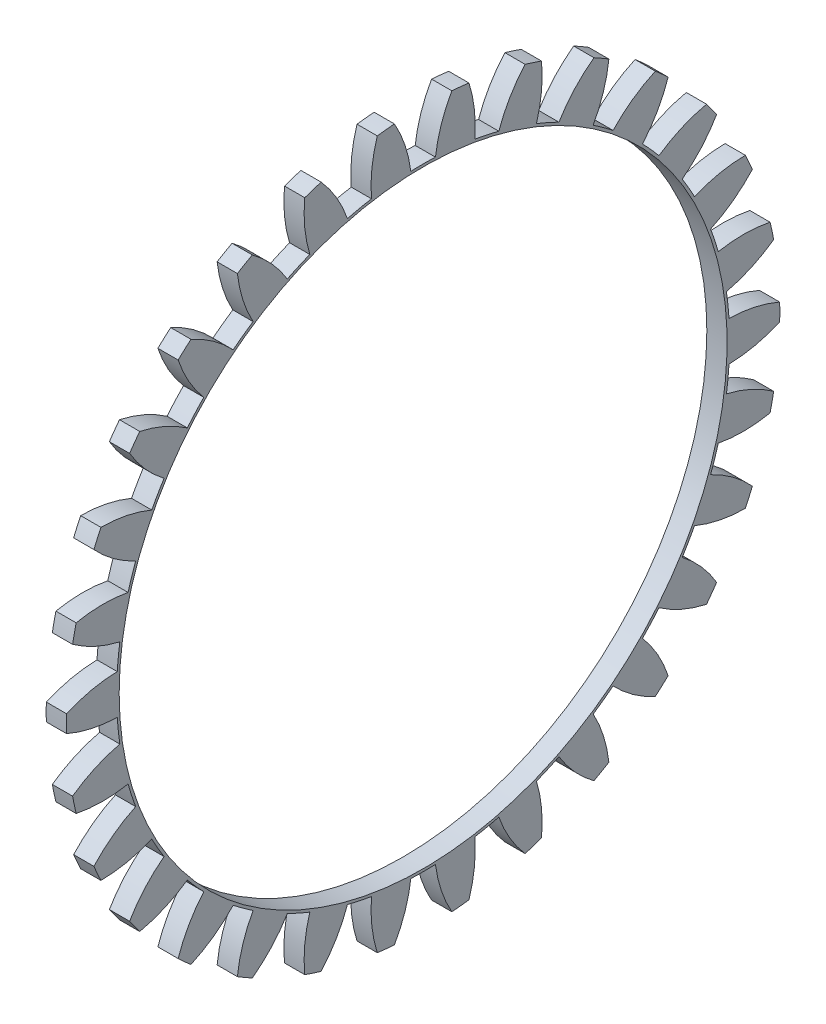
SolidWorks part; units mm, degrees
ref_plane "Plane1" through (0, 0, 0) normal (0, 0, 1) x (1, 0, 0)
ref_plane "Plane2" through (0, 0, 0) normal (0, 1, 0) x (1, 0, 0)
ref_plane "Plane3" through (0, 0, 0) normal (1, 0, 0) x (0, 0, -1)
other "Configuration Table"
sketch "HoldingSke" plane through (0, 0, 0) normal (0, 1, 0) x (1, 0, 0)
  line L0 (0, 0) -> (0.1575, -0.0909)
  line L1 (-15, 0) -> (100, 0) construction
  line L2 (0, 0) -> (-2.1039, 2.3779)
  line L3 (0, 0) -> (-11.863, 4.5341)
  line L4 (0, 0) -> (7.479, 4.318)
  line L5 (0, 0) -> (-46.8476, -17.4728)
  line L6 (0, 0) -> (-4.1448, -2.7965)
  line L7 (-2.1039, 2.3779) -> (8.6586, 51.2059)
  line L8 (-76.2, 54.61) -> (-66.8, 54.61)
  line L9 (-67.7845, 28.3722) -> (-49.3413, 33.142)
  line L10 (-76.2, 71.12) -> (104.1128, 71.12)
  line L11 (0, 0) -> (-5, 0)
  line L12 (-76.2, 101.6) -> (-76.013, 101.6)
  line L13 (24.9733, 27.94) -> (52.9518, 28.4284)
  line L14 (24.9733, 27.94) -> (24.9743, 27.94)
  line L15 (24.9733, 27.94) -> (100.4006, 29.5858)
  line L16 (-63.627, -5.5) -> (-12.827, -5.5)
  circle A0 centre (0, 0) radius 75
  circle A1 centre (0, 0) radius 37.5
  circle A2 centre (0, 0) radius 37.5
  circle A3 centre (0, 0) radius 75
  dimension "MHD" = 75
  dimension "Hub_dia" = 75
  dimension "Bore" = 150
  dimension "MBD" = 150
  dimension "Num_teeth" = 30
  dimension "Pitch" = 0.1818
  dimension "Overall_len" = 50
  dimension "Show_teeth" = 30
  dimension "Thickness" = 5
  dimension "OAL" = 50.0001
  dimension "T_dim" = 9.4
  dimension "Ap" = 14.5
  dimension "H" = 19.05
  dimension "Pitch_radius" = 180.3128
  dimension "Width" = 5
  dimension "Backlash" = 0.187
  dimension "Addendum_fac" = 1
  dimension "Dedendum_fac" = 1.25
  dimension "Clearance_fac" = 0.25
  dimension "Dedendum_add" = 0.001
  dimension "Module" = 5.5
sketch "BasProSke" plane through (0, 0, 0) normal (0, 1, 0) x (1, 0, 0)
  line L0 (-10, 0) -> (60, 0) construction
  line L1 (0, 0) -> (0, 88)
  line L2 (0, 0) -> (5, 0)
  line L3 (5, 0) -> (5, 88)
  line L4 (5, 88) -> (0, 88)
  dimension "Thickness" = 5
  dimension "Diameter" = 176
revolve "Base-Revolve" add sketch "BasProSke" angle 360 about L0
sketch "TooCutSke" plane through (0, 0, 0) normal (1, 0, 0) x (0, 0, -1)
  line L1 (0, 0) -> (0, 107) construction
  line L2 (0, 0) -> (-4.6449, 82.3691) construction
  line L3 (0, 0) -> (-17.227, 163.904) construction
  line L4 (-4.6449, 82.3691) -> (-8.6135, 81.952) construction
  arc A0 (3.0351, 75.5631) -> (-3.0351, 75.5631) centre (0, 0) ccw
  arc A1 (7.0945, 87.739) -> (-7.0945, 87.739) centre (0, 0) ccw
  circle A2 centre (0, 0) radius 82.5 construction
  circle A3 centre (0, 0) radius 79.8722 construction
  arc A4 (-3.0351, 75.5631) -> (-7.0945, 87.739) centre (-35.7731, 71.4132) ccw
  arc A5 (7.0945, 87.739) -> (3.0351, 75.5631) centre (35.7731, 71.4132) ccw
  dimension "Root_dia" = 151.248
  dimension "Overcut_dia" = 176.0508
  dimension "Pitch_dia" = 165
  dimension "Base_dia" = 159.7444
  dimension "Flank_rad" = 33
  dimension "Half_ang" = 6
  dimension "Half_CT" = 3.9905
extrude "ToothCut" cut sketch "TooCutSke" along normal through all
fillet "Breaks" [suppressed] radius 0.11
fillet "RootFillets" [suppressed] radius 1.376
pattern_circular "TeethCuts" count 30 every 12 about axis through (-10, 0, 0) along (1, 0, 0) of "ToothCut", "RootFillets", "Breaks"
sketch "HubNeaOneSke" plane through (0, 0, 0) normal (-1, 0, 0) x (0, 0, 1)
  circle A0 centre (0, 0) radius 37.5
  dimension "Diameter" = 75
extrude "HubNearOne" [suppressed] add sketch "HubNeaOneSke" along normal blind 45.0001
sketch "HubNeaBotSke" plane through (0, 0, 0) normal (-1, 0, 0) x (0, 0, 1)
  circle A0 centre (0, 0) radius 37.5
  dimension "Diameter" = 75
extrude "HubNearBoth" [suppressed] add sketch "HubNeaBotSke" along normal blind 22.5
ref_plane "FarPln" through (5, 0, 0) normal (1, 0, 0) x (0, 0, -1)
sketch "HubFarSke" plane through (5, 0, 0) normal (1, 0, 0) x (0, 0, -1)
  circle A0 centre (0, 0) radius 37.5
  dimension "Diameter" = 75
extrude "HubFar" [suppressed] add sketch "HubFarSke" along normal blind 22.5
sketch "BorSke" plane through (0, 0, 0) normal (1, 0, 0) x (0, 0, -1)
  circle A0 centre (0, 0) radius 75
  dimension "Diameter" = 150
extrude "Bore" cut sketch "BorSke" along normal mid plane 100.0001
sketch "KeySke" plane through (0, 0, 0) normal (1, 0, 0) x (0, 0, -1)
  line L0 (-20, 0) -> (-20, 84.4)
  line L1 (-20, 84.4) -> (20, 84.4)
  line L2 (20, 84.4) -> (20, 0)
  line L3 (0, 0) -> (0, 34) construction
  line L4 (-20, 0) -> (20, 0)
  dimension "Offset" = 84.4
  dimension "Width" = 40
extrude "Keyway" [suppressed] cut sketch "KeySke" along normal mid plane 100.0001
pattern_circular "Keyway2" [suppressed] count 2 every 90 about axis through (-10, 0, 0) along (1, 0, 0)
equation "' \"Module@HoldingSke\" = 6.35"
equation "' \"Num_teeth@HoldingSke\" = 12"
equation "' \"Ap@HoldingSke\" =  20"
equation "' \"Ap@HoldingSke\" = 20"
equation "' \"Width@HoldingSke\" = 0.5 * 25.4"
equation "' \"Hub_dia@HoldingSke\"= 1 * 25.4"
equation "' \"Hub_dia@HoldingSke\" = 1 * 25.4"
equation "' \"Overall_len@HoldingSke\" = 1.0 * 25.4"
equation "' \"Bore@HoldingSke\" = 0.75 * 25.4"
equation "' \"T_dim@HoldingSke\" = 0.1 * 25.4"
equation "' \"Width@KeySke\" = 0.25 * 25.4"
equation "' \"Show_teeth@HoldingSke\" = 13"
equation "' \"Backlash@HoldingSke\" = 0.009 * 25.4"
equation "' \"Addendum_fac@HoldingSke\" = 1.0"
equation "' \"Dedendum_fac@HoldingSke\" = 1.25"
equation "' \"Dedendum_add@HoldingSke\" = 0.00005 * 25.4"
equation "' \"Clearance_fac@HoldingSke\" = 0.25"
equation "\"Pitch@HoldingSke\" = 1 / \"Module@HoldingSke\""
equation "\"Overcut_dia@TooCutSke\" = (\"Num_teeth@HoldingSke\" + 2 * \"Addendum_fac@HoldingSke\") / \"Pitch@HoldingSke\" + 0.002 * 25.4"
equation "\"Pitch_dia@TooCutSke\" = \"Num_teeth@HoldingSke\" / \"Pitch@HoldingSke\""
equation "\"Base_dia@TooCutSke\" = \"Num_teeth@HoldingSke\" / \"Pitch@HoldingSke\" * cos((\"Ap@HoldingSke\"  * 3.14159265 / 180))"
equation "\"Root_dia@TooCutSke\" = (\"Num_teeth@HoldingSke\" + 2) / \"Pitch@HoldingSke\" - 2 * (\"Addendum_fac@HoldingSke\" + \"Dedendum_fac@HoldingSke\") / \"Pitch@HoldingSke\" - \"Dedendum_add@HoldingSke\" * 2"
equation "\"Half_ang@TooCutSke\" = 180 / \"Num_teeth@HoldingSke\""
equation "\"Half_CT@TooCutSke\" = \"Num_teeth@HoldingSke\" / \"Pitch@HoldingSke\" * sin((3.14159265 / 2 / \"Num_teeth@HoldingSke\")) / 2 - 7 * \"Backlash@HoldingSke\" / 4"
equation "\"Flank_rad@TooCutSke\" = \"Num_teeth@HoldingSke\" / \"Pitch@HoldingSke\" / 5"
equation "\"Radius@RootFillets\" = \"Clearance_fac@HoldingSke\" / \"Pitch@HoldingSke\" + \"Dedendum_add@HoldingSke\""
equation "\"Break_rad@Breaks\" = 0.02 / \"Pitch@HoldingSke\""
equation "\"Thickness@HoldingSke\" = \"Width@HoldingSke\""
equation "\"OAL@HoldingSke\" = \"Thickness@HoldingSke\""
equation "\"MHD@HoldingSke\" = (\"Num_teeth@HoldingSke\" + 2) / \"Pitch@HoldingSke\" - 2 * (\"Addendum_fac@HoldingSke\" + \"Dedendum_fac@HoldingSke\")  / \"Pitch@HoldingSke\" - \"Dedendum_add@HoldingSke\" * 2"
equation "\"MBD@HoldingSke\" = (\"Num_teeth@HoldingSke\" + 2) / \"Pitch@HoldingSke\" - 2 * (\"Addendum_fac@HoldingSke\" + \"Dedendum_fac@HoldingSke\")  / \"Pitch@HoldingSke\" - \"Dedendum_add@HoldingSke\" * 2 - 0.002 * 25.4"
equation "\"MHD@HoldingSke\" = ((sgn( \"MHD@HoldingSke\" - \"Hub_dia@HoldingSke\" )-1)*( \"MHD@HoldingSke\" - \"Hub_dia@HoldingSke\" ))/-2+ \"Hub_dia@HoldingSke\""
equation "\"MBD@HoldingSke\" = ((sgn( \"MBD@HoldingSke\" - \"Bore@HoldingSke\" )-1)*( \"MBD@HoldingSke\" - \"Bore@HoldingSke\" ))/-2+ \"Bore@HoldingSke\""
equation "\"OAL@HoldingSke\" = ((sgn( \"OAL@HoldingSke\" - \"Overall_len@HoldingSke\" )+1)*( \"OAL@HoldingSke\" - \"Overall_len@HoldingSke\" ))/2 + \"Overall_len@HoldingSke\" + 0.000002 * 25.4"
equation "\"Num_teeth@TeethCuts\" = int( \"Show_teeth@HoldingSke\" ) + 1"
equation "\"Num_teeth@TeethCuts\" = ((sgn( \"Num_teeth@TeethCuts\" - \"Num_teeth@HoldingSke\" )-1)*( \"Num_teeth@TeethCuts\" - \"Num_teeth@HoldingSke\" ))/-2+ \"Num_teeth@HoldingSke\""
equation "\"Num_teeth@TeethCuts\" = ((sgn( \"Num_teeth@TeethCuts\" - 2.0)+1)*( \"Num_teeth@TeethCuts\" - 2.0))/2 +2.0"
equation "\"Angle@TeethCuts\" = 360.0 / \"Num_teeth@HoldingSke\""
equation "\"Diameter@BasProSke\" = (\"Num_teeth@HoldingSke\" + 2 * \"Addendum_fac@HoldingSke\") / \"Pitch@HoldingSke\""
equation "\"Thickness@BasProSke\"  = \"Thickness@HoldingSke\""
equation "' \"Fillet_rad@BasProSke\" =  \"Thickness@HoldingSke\" * 0.05"
equation "' \"Fillet_rad@BasProSke\" = \"Thickness@HoldingSke\" * 0.05"
equation "\"MHD@HoldingSke\" = ((sgn( \"MHD@HoldingSke\" - \"Root_dia@TooCutSke\" )-1)*( \"MHD@HoldingSke\" - \"Root_dia@TooCutSke\" ))/-2+ \"Root_dia@TooCutSke\""
equation "\"Diameter@HubNeaOneSke\" = \"MHD@HoldingSke\""
equation "\"Length@HubNearOne\" = \"OAL@HoldingSke\" - \"Thickness@BasProSke\""
equation "\"Diameter@HubNeaBotSke\" = \"MHD@HoldingSke\""
equation "\"Length@HubNearBoth\" = ( \"OAL@HoldingSke\" - \"Thickness@BasProSke\" ) / 2.0"
equation "\"Thickness@FarPln\" = \"Thickness@BasProSke\""
equation "\"Diameter@HubFarSke\" = \"MHD@HoldingSke\""
equation "\"Length@HubFar\" = ( \"OAL@HoldingSke\" - \"Thickness@BasProSke\" ) / 2.0"
equation "\"Diameter@BorSke\" = \"MBD@HoldingSke\""
equation "\"D1@Bore\" = \"OAL@HoldingSke\" * 2.0"
equation "\"D1@Keyway\" = \"OAL@HoldingSke\" * 2.0"
equation "\"Offset@KeySke\" = \"T_dim@HoldingSke\" + \"MBD@HoldingSke\" / 2.0"
